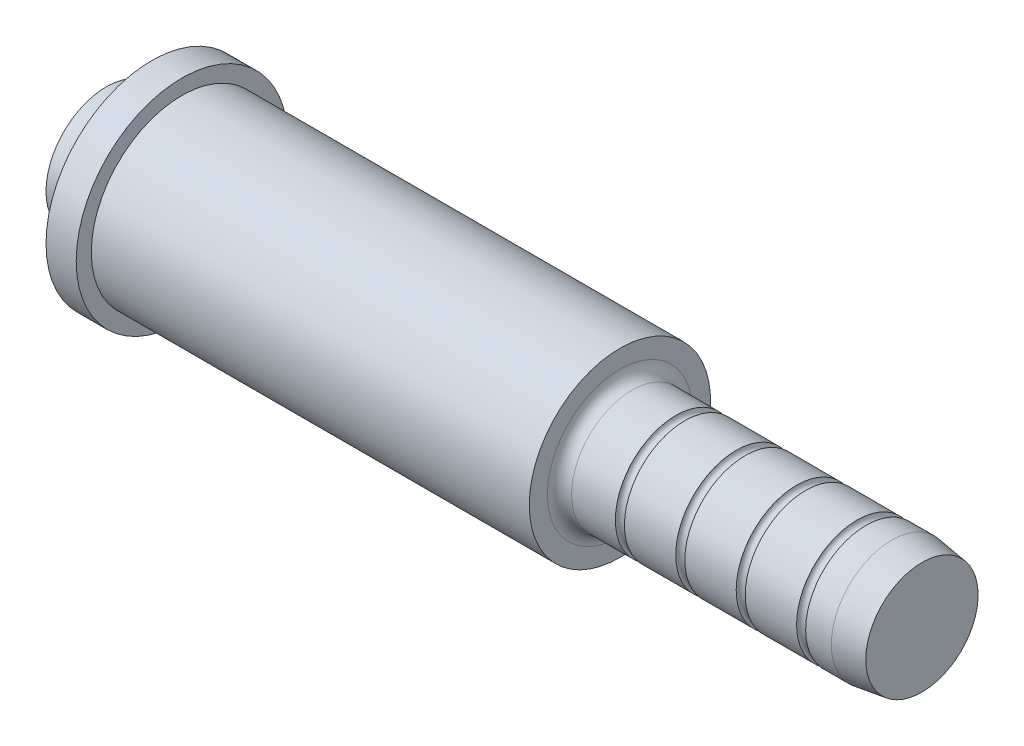
SolidWorks part; units mm, degrees
material "AISI 1015 Steel, Cold Drawn (SS)"
ref_plane "Front Plane" through (0, 0, 0) normal (0, 0, 1) x (1, 0, 0)
ref_plane "Top Plane" through (0, 0, 0) normal (0, 1, 0) x (1, 0, 0)
ref_plane "Right Plane" through (0, 0, 0) normal (1, 0, 0) x (0, 0, -1)
sketch "Sketch1" plane through (0, 0, 0) normal (0, 0, 1) x (1, 0, 0)
  line L0 (0, 0) -> (270, 0)
  line L1 (0, 20) -> (15, 20)
  line L2 (0, 0) -> (0, 20)
  line L3 (15, 35) -> (25, 35)
  line L4 (15, 20) -> (15, 35)
  line L5 (25, 30) -> (170, 30)
  line L6 (25, 35) -> (25, 30)
  line L7 (170, 20) -> (270, 20)
  line L8 (170, 30) -> (170, 20)
  line L9 (270, 20) -> (270, 0)
  dimension "D1" = 20
  dimension "D2" = 30
  dimension "D3" = 35
  dimension "D4" = 20
revolve "Revolve1" add sketch "Sketch1" angle 360 about L0
fillet "Fillet1" radius 4 1 edges at (170, 0, 20)
chamfer "Chamfer1" distance 10 angle 8 1 edges at (270, 0, 20)
sketch "Sketch2" plane through (0, 0, 0) normal (0, 0, 1) x (1, 0, 0)
  line L0 (260, 20) -> (174, 20) construction
  line L1 (170, -24) -> (170, 24) construction
  circle A0 centre (190, 20) radius 1.5
  circle A1 centre (210, 20) radius 1.5
  circle A2 centre (230, 20) radius 1.5
  circle A3 centre (250, 20) radius 1.5
  dimension "D1" = 20
  dimension "D2" = 4
ref_axis "Axis1" through (170, 0, 0) along (-1, 0, 0)
revolve "Cut-Revolve1" cut sketch "Sketch2" angle 360 about axis through (170, 0, 0) along (-1, 0, 0)
